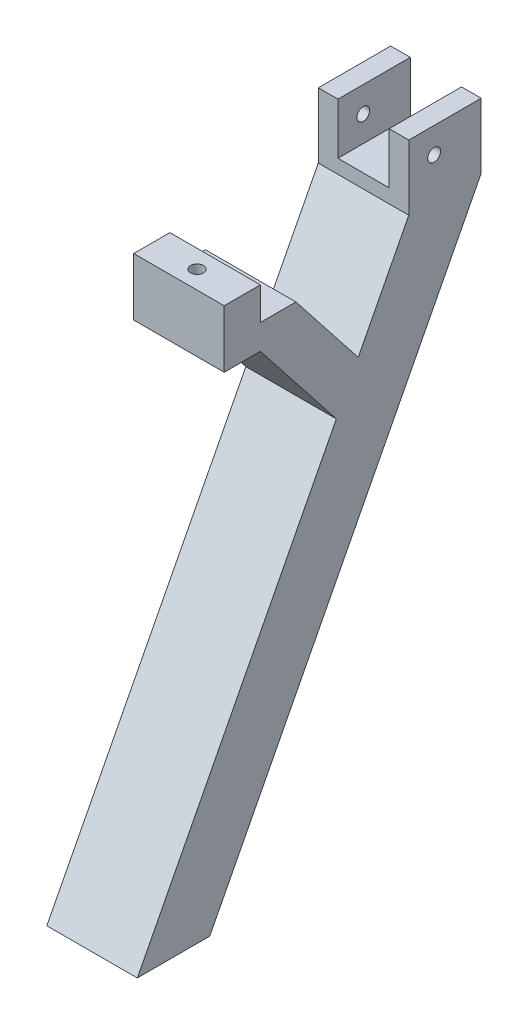
SolidWorks part; units mm, degrees
ref_plane "Front Plane" through (0, 0, 0) normal (0, 0, 1) x (1, 0, 0)
ref_plane "Top Plane" through (0, 0, 0) normal (0, 1, 0) x (1, 0, 0)
ref_plane "Right Plane" through (0, 0, 0) normal (1, 0, 0) x (0, 0, -1)
sketch "Sketch1" plane through (0, 0, 0) normal (1, 0, 0) x (0, 0, -1)
  line L0 (-75.8279, -173.4273) -> (-55.8279, -173.4273)
  line L1 (-55.8279, -173.4273) -> (-55.8279, -191.4273)
  line L2 (-55.8279, -191.4273) -> (-130.8279, -336.4273)
  line L3 (-130.8279, -336.4273) -> (-150.8279, -336.4273)
  line L4 (-150.8279, -336.4273) -> (-91.8279, -222.3606)
  line L5 (-75.8279, -191.4273) -> (-75.8279, -173.4273)
  line L6 (-75.8279, -191.4273) -> (-55.8279, -191.4273) construction
  line L7 (-91.8279, -222.3606) -> (-75.8279, -191.4273)
  dimension "D1" = 20
  dimension "D2" = 18
  dimension "D3" = 145
  dimension "D4" = 75
extrude "Boss-Extrude1" add sketch "Sketch1" along normal blind 25
sketch "Sketch5" plane through (0, 0, 75.8279) normal (0, 0, 1) x (1, 0, 0)
  line L0 (25, -173.4273) -> (0, -173.4273) construction
  line L1 (5.425, -173.4273) -> (19.575, -173.4273)
  line L2 (5.425, -173.4273) -> (5.425, -187.5773)
  line L3 (5.425, -187.5773) -> (19.575, -187.5773)
  line L4 (19.575, -173.4273) -> (19.575, -187.5773)
  line L5 (0, -173.4273) -> (5.425, -173.4273) construction
  line L6 (19.575, -173.4273) -> (25, -173.4273) construction
  dimension "D1" = 14.15
extrude "Cut-Extrude4" cut sketch "Sketch5" against normal through all
sketch "Sketch6" plane through (25, 0, 0) normal (1, 0, 0) x (0, 0, -1)
  line L0 (-68.8279, -173.4273) -> (-68.8279, -187.5273) construction
  line L2 (-75.8279, -173.4273) -> (-75.8279, -191.4273) construction
  circle A0 centre (-68.8279, -180.4773) radius 1.775
  dimension "D2" = 3.55
  dimension "D1" = 14.1
  dimension "D3" = 7
extrude "Cut-Extrude5" cut sketch "Sketch6" against normal up to surface (25 mm away) up to face at (0, -233.7606, 90.8279)
sketch "Sketch8" plane through (25, 0, 0) normal (1, 0, 0) x (0, 0, -1)
  line L0 (-121.8279, -187.5773) -> (-121.8279, -196.5773) construction
  line L1 (-126.8279, -187.5773) -> (-116.8279, -187.5773)
  line L2 (-126.8279, -187.5773) -> (-126.8279, -196.5773)
  line L3 (-116.8279, -196.5773) -> (-107.008, -196.5773)
  line L4 (-116.8279, -187.5773) -> (-116.8279, -196.5773)
  line L5 (-55.8279, -187.5773) -> (-75.8279, -187.5773) construction
  line L7 (-107.008, -196.5773) -> (-89.7934, -218.4273)
  line L8 (-91.8279, -222.3606) -> (-75.8279, -191.4273) construction
  line L9 (-126.8279, -196.5773) -> (-116.8279, -196.5773) construction
  line L10 (-89.7934, -218.4273) -> (-95.848, -230.1328)
  line L11 (-150.8279, -336.4273) -> (-91.8279, -222.3606) construction
  line L12 (-95.848, -230.1328) -> (-116.8279, -203.5037)
  line L13 (-116.8279, -203.5037) -> (-126.8279, -203.5037)
  line L14 (-126.8279, -203.5037) -> (-126.8279, -196.5773)
  circle A0 centre (-68.8279, -180.4773) radius 1.775 construction
  dimension "D1" = 9
  dimension "D2" = 10
  dimension "D3" = 53
  dimension "D4" = 27
  dimension "D5" = 12
extrude "Boss-Extrude2" add sketch "Sketch8" against normal blind 25
sketch "Sketch9" plane through (0, -187.5773, 0) normal (0, 1, 0) x (1, 0, 0)
  line L0 (12.5, -126.8279) -> (12.5, -116.8279) construction
  line L1 (0, -126.8279) -> (25, -126.8279) construction
  line L2 (0, -116.8279) -> (25, -116.8279) construction
  circle A0 centre (12.5, -121.8279) radius 1.775
  dimension "D1" = 3.55
extrude "Cut-Extrude6" cut sketch "Sketch9" against normal up to surface (15.9264 mm away) up to face at (12.5, -203.5037, 121.8279)
